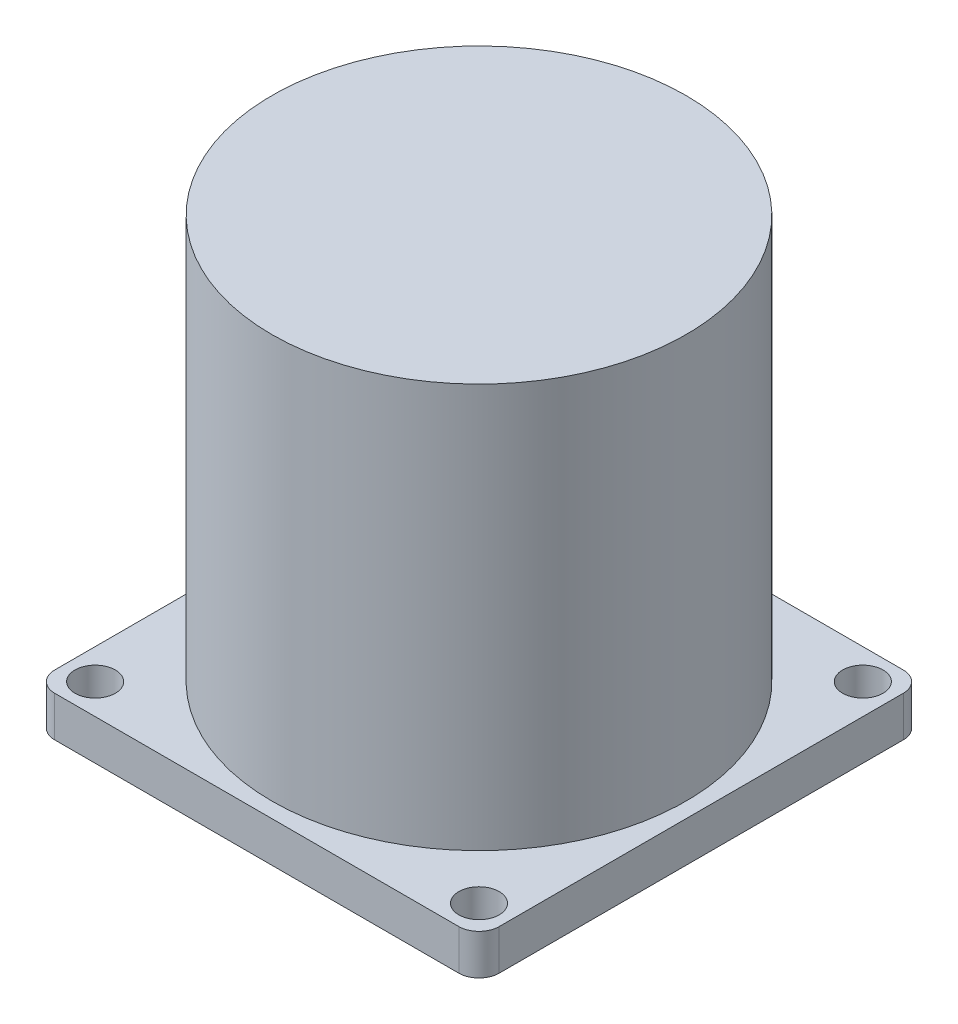
SolidWorks part; units mm, degrees
material "6061 Alloy"
ref_plane "Front Plane" through (0, 0, 0) normal (0, 0, 1) x (1, 0, 0)
ref_plane "Top Plane" through (0, 0, 0) normal (0, 1, 0) x (1, 0, 0)
ref_plane "Right Plane" through (0, 0, 0) normal (1, 0, 0) x (0, 0, -1)
sketch "Sketch1" plane through (0, 0, 0) normal (0, 1, 0) x (1, 0, 0)
  line L5 (-95, 95) -> (95, 95) construction
  line L6 (-95, 95) -> (-95, -95) construction
  line L7 (-95, -95) -> (95, -95) construction
  line L8 (95, 95) -> (95, -95) construction
  line L9 (-95, 95) -> (95, -95) construction
  line L10 (-95, -95) -> (95, 95) construction
  line L11 (-110, 110) -> (110, 110)
  line L12 (-110, 110) -> (-110, -110)
  line L13 (-110, -110) -> (110, -110)
  line L14 (110, 110) -> (110, -110)
  line L15 (-110, 110) -> (110, -110) construction
  line L16 (-110, -110) -> (110, 110) construction
  circle A0 centre (-95, 95) radius 10
  circle A1 centre (95, 95) radius 10
  circle A2 centre (95, -95) radius 10
  circle A3 centre (-95, -95) radius 10
  point P1 (0, 0)
  point P6 (0, 0)
  point P15 (0, 0)
  dimension "D3" = 220
  dimension "D1" = 190
  dimension "D2" = 190
  dimension "D4" = 220
extrude "Boss-Extrude2" add sketch "Sketch1" along normal blind 20
fillet "Fillet5" radius 10 4 edges at (110, 10, 110) (110, 10, -110) (-110, 10, -110) (-110, 10, 110)
sketch "Sketch6" plane through (0, 20, 0) normal (0, 1, 0) x (1, 0, 0)
  circle A0 centre (0, 0) radius 102.5
extrude "Boss-Extrude3" add sketch "Sketch6" along normal blind 200
ref_point "Point1"
